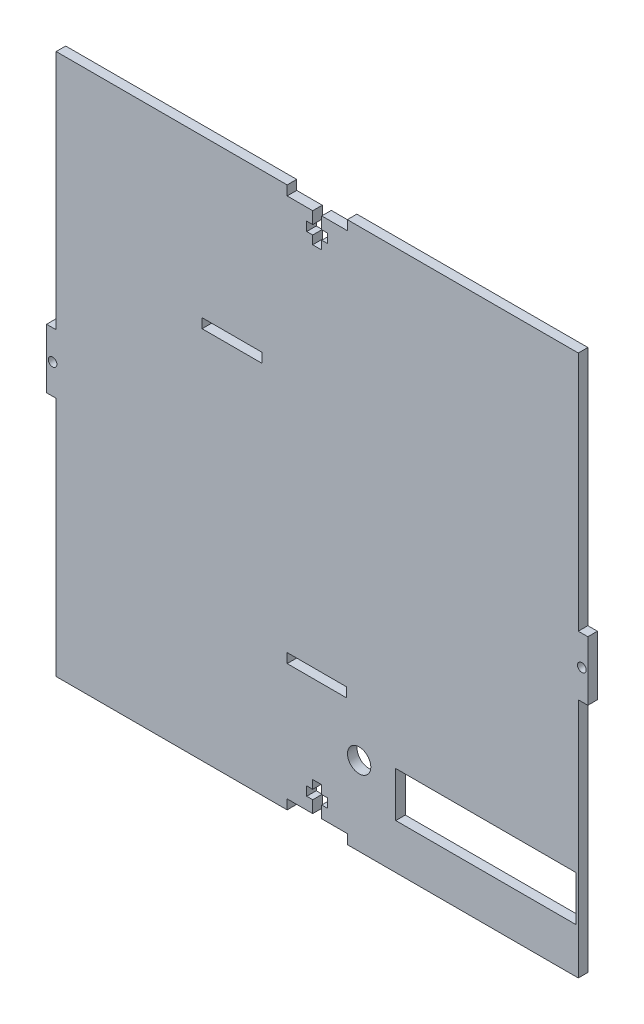
SolidWorks part; units mm, degrees
ref_plane "Front Plane" through (0, 0, 0) normal (0, 0, 1) x (1, 0, 0)
ref_plane "Top Plane" through (0, 0, 0) normal (0, 1, 0) x (1, 0, 0)
ref_plane "Right Plane" through (0, 0, 0) normal (1, 0, 0) x (0, 0, -1)
sketch "Sketch3" plane through (0, 0, 0) normal (0, 0, 1) x (1, 0, 0)
  line L0 (-18.2869, 37.6148) -> (-18.2869, 34.4348)
  line L1 (-90, 90) -> (90, 90)
  line L2 (-90, 90) -> (-90, -90)
  line L3 (-90, -90) -> (90, -90)
  line L4 (90, 90) -> (90, -90)
  line L5 (-18.2869, 34.4348) -> (-38.2869, 34.4348)
  line L6 (-38.2869, 34.4348) -> (-38.2869, 37.6148)
  line L7 (-38.2869, 37.6148) -> (-18.2869, 37.6148)
  line L8 (9.75, -44.6797) -> (9.75, -47.8597)
  line L9 (9.75, -47.8597) -> (-10, -47.8597)
  line L10 (-10, -47.8597) -> (-10, -44.6797)
  line L11 (-10, -44.6797) -> (9.75, -44.6797)
  line L14 (86.1129, -60.0147) -> (26.1129, -60.0147)
  line L15 (86.1129, -60.0147) -> (86.1129, -75.0147)
  line L16 (86.1129, -75.0147) -> (26.1129, -75.0147)
  line L17 (26.1129, -60.0147) -> (26.1129, -75.0147)
  circle A4 centre (13.9387, -63.7582) radius 3.875
  dimension "D2" = 60
  dimension "D11" = 7.75
  dimension "D1" = 180
  dimension "D3" = 180
  dimension "D4" = 15
extrude "Boss-Extrude1" add sketch "Sketch3" along normal blind 3.18
sketch "Sketch4" plane through (0, 0, 3.18) normal (0, 0, 1) x (1, 0, 0)
  line L0 (-90, 90) -> (-90, -90) construction
  line L1 (90, -90) -> (90, 90) construction
  line L2 (-90, 0) -> (90, 0) construction
  line L3 (0.9399, -90) -> (0, -90) construction
  line L4 (90, 90) -> (-90, 90) construction
  line L5 (0, -90) -> (0, 90) construction
  line L6 (1.5, 86.82) -> (10, 86.82)
  line L7 (-10, 90) -> (10, 90)
  line L8 (-10, 90) -> (-10, 86.82)
  line L9 (-10, 86.82) -> (-1.5, 86.82)
  line L10 (10, 90) -> (10, 86.82)
  line L11 (-3.5, 82.82) -> (-1.5, 82.82)
  line L12 (-3.5, 82.82) -> (-3.5, 79.82)
  line L13 (-3.5, 79.82) -> (-1.5, 79.82)
  line L14 (3.5, 82.82) -> (3.5, 79.82)
  line L15 (1.5, 82.82) -> (3.5, 82.82)
  line L16 (-1.5, 86.82) -> (-1.5, 82.82)
  line L17 (-1.5, 77) -> (1.5, 77)
  line L18 (1.5, 86.82) -> (1.5, 82.82)
  line L19 (-90, -90) -> (90, -90) construction
  line L20 (1.5, 79.82) -> (3.5, 79.82)
  line L21 (-1.5, 79.82) -> (-1.5, 77)
  line L22 (1.5, 79.82) -> (1.5, 77)
  line L23 (1.5, -79.82) -> (1.5, -77)
  line L24 (-1.5, -79.82) -> (-1.5, -77)
  line L25 (1.5, -79.82) -> (3.5, -79.82)
  line L26 (1.5, -86.82) -> (1.5, -82.82)
  line L27 (-1.5, -77) -> (1.5, -77)
  line L28 (-1.5, -86.82) -> (-1.5, -82.82)
  line L29 (1.5, -82.82) -> (3.5, -82.82)
  line L30 (3.5, -82.82) -> (3.5, -79.82)
  line L31 (-3.5, -79.82) -> (-1.5, -79.82)
  line L32 (-3.5, -82.82) -> (-3.5, -79.82)
  line L33 (-3.5, -82.82) -> (-1.5, -82.82)
  line L34 (10, -90) -> (10, -86.82)
  line L35 (-10, -86.82) -> (-1.5, -86.82)
  line L36 (-10, -90) -> (-10, -86.82)
  line L37 (-10, -90) -> (10, -90)
  line L38 (1.5, -86.82) -> (10, -86.82)
  dimension "D1" = 20
  dimension "D2" = 3.18
  dimension "D3" = 4
  dimension "D4" = 3
  dimension "D5" = 3
  dimension "D6" = 13
  dimension "D7" = 7
sketch "Sketch5" plane through (0, 0, 3.18) normal (0, 0, 1) x (1, 0, 0)
  line L0 (-90, 0) -> (90, 0) construction
  line L1 (-90, 90) -> (-86.82, 90)
  line L2 (-90, 90) -> (-90, 9.875)
  line L3 (-90, 9.875) -> (-86.82, 9.875)
  line L4 (-86.82, 90) -> (-86.82, 9.875)
  line L5 (-90, -90) -> (-86.82, -90)
  line L6 (-90, -90) -> (-90, -9.875)
  line L7 (-90, -9.875) -> (-86.82, -9.875)
  line L8 (-86.82, -90) -> (-86.82, -9.875)
  line L9 (-90, 90) -> (-90, -90) construction
  line L10 (0, 90) -> (0, -90) construction
  line L11 (86.82, -90) -> (86.82, -9.875)
  line L12 (90, -9.875) -> (86.82, -9.875)
  line L13 (90, -90) -> (90, -9.875)
  line L14 (90, -90) -> (86.82, -90)
  line L15 (86.82, 90) -> (86.82, 9.875)
  line L16 (90, 9.875) -> (86.82, 9.875)
  line L17 (90, 90) -> (90, 9.875)
  line L18 (90, 90) -> (86.82, 90)
  circle A0 centre (-88, 0) radius 1.436
  circle A1 centre (88, 0) radius 1.436
  dimension "D4" = 2.872
  dimension "D5" = 2
  dimension "D1" = 3.18
  dimension "D2" = 3.18
  dimension "D3" = 19.75
extrude "Cut-Extrude1" cut sketch "Sketch4" against normal through all
extrude "Cut-Extrude2" cut sketch "Sketch5" against normal through all
